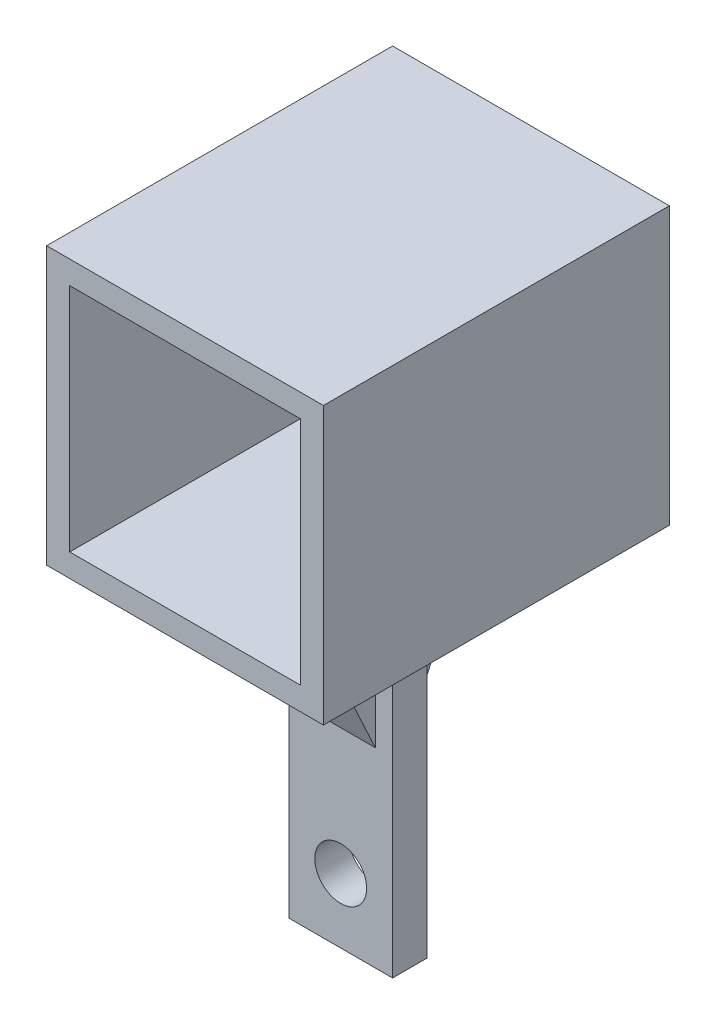
SolidWorks part; units mm, degrees
ref_plane "Alzado" through (0, 0, 0) normal (0, 0, 1) x (1, 0, 0)
ref_plane "Planta" through (0, 0, 0) normal (0, 1, 0) x (1, 0, 0)
ref_plane "Vista lateral" through (0, 0, 0) normal (1, 0, 0) x (0, 0, -1)
sketch "Croquis1" plane through (0, 0, 0) normal (0, 0, 1) x (1, 0, 0)
  line L0 (0, 0) -> (0, 25.9) construction
  line L1 (-10, 25.9) -> (10, 25.9) construction
  line L2 (0, 0) -> (-4.5, 0) construction
  line L3 (0, 0) -> (4.5, 0) construction
  line L4 (-4.5, 0) -> (-4.5, -5.6) construction
  line L5 (-4.5, -5.6) -> (4.5, -5.6)
  line L6 (-4.5, -5.6) -> (-4.5, 25.9)
  line L7 (4.5, -5.6) -> (4.5, 25.9)
  line L8 (-4.5, 25.9) -> (4.5, 25.9)
  circle A0 centre (0, 0) radius 2.25
  point P7 (0, 25.9)
  dimension "D1" = 4.5
  dimension "D2" = 25.9
  dimension "D3" = 20
  dimension "D4" = 4.5
  dimension "D5" = 4.5
  dimension "D6" = 31.5
extrude "Saliente-Extruir1" add sketch "Croquis1" along normal mid plane 3
sketch "Croquis11" plane through (0, 0, 0) normal (0, 0, 1) x (1, 0, 0)
  line L0 (0, 25.9) -> (0, 45.9) construction
  line L2 (4.5, 25.9) -> (-4.5, 25.9) construction
  line L4 (-10, 25.9) -> (10, 25.9)
  line L5 (-10, 25.9) -> (-10, 45.9)
  line L6 (-10, 45.9) -> (10, 45.9)
  line L7 (10, 25.9) -> (10, 45.9)
  line L8 (-10, 25.9) -> (10, 45.9) construction
  line L9 (-10, 45.9) -> (10, 25.9) construction
  line L10 (-12, 23.9) -> (12, 23.9)
  line L11 (-12, 23.9) -> (-12, 47.9)
  line L12 (-12, 47.9) -> (12, 47.9)
  line L13 (12, 23.9) -> (12, 47.9)
  line L14 (-12, 23.9) -> (12, 47.9) construction
  line L15 (-12, 47.9) -> (12, 23.9) construction
  point P2 (0, 35.9)
  point P9 (0, 35.9)
  dimension "D1" = 20
  dimension "D2" = 20
  dimension "D3" = 20
  dimension "D4" = 24
  dimension "D5" = 24
extrude "Saliente-Extruir8" add sketch "Croquis11" along normal mid plane 30
sketch "Croquis13" plane through (0, 0, 0) normal (1, 0, 0) x (0, 0, -1)
  line L0 (1.5, 23.9) -> (1.5, 10.95) construction
  line L5 (-15, 23.9) -> (15, 23.9) construction
  line L6 (1.5, 23.9) -> (1.5, -5.6) construction
  line L7 (0, 23.9) -> (0, 15.712) construction
  line L8 (1.5, 10.95) -> (1.5, 23.9)
  line L9 (-7.5, 23.9) -> (-1.5, 10.95)
  line L10 (-1.5, 23.9) -> (-7.5, 23.9)
  line L11 (-1.5, 10.95) -> (-1.5, 23.9)
  line L21 (1.5, 23.9) -> (7.5, 23.9)
  line L22 (7.5, 23.9) -> (1.5, 10.95)
  dimension "D1" = 12.95
  dimension "D2" = 6
extrude "Saliente-Extruir11" add sketch "Croquis13" along normal mid plane 6
